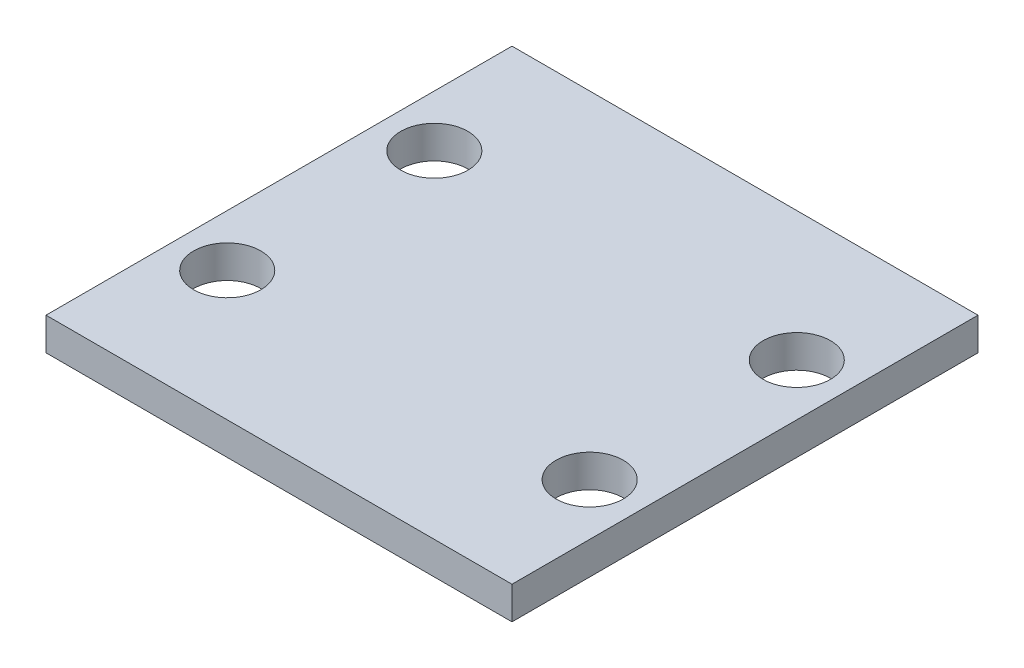
SolidWorks part; units mm, degrees
ref_plane "Front Plane" through (0, 0, 0) normal (0, 0, 1) x (1, 0, 0)
ref_plane "Top Plane" through (0, 0, 0) normal (0, 1, 0) x (1, 0, 0)
ref_plane "Right Plane" through (0, 0, 0) normal (1, 0, 0) x (0, 0, -1)
sketch "Sketch1" plane through (0, 0, 0) normal (0, 1, 0) x (1, 0, 0)
  line L1 (-11.43, -11.43) -> (11.43, -11.43)
  line L2 (-11.43, -11.43) -> (-11.43, 11.43)
  line L3 (-11.43, 11.43) -> (11.43, 11.43)
  line L4 (11.43, -11.43) -> (11.43, 11.43)
  line L5 (-11.43, -11.43) -> (11.43, 11.43) construction
  line L6 (-11.43, 11.43) -> (11.43, -11.43) construction
  line L7 (8.89, -5.08) -> (-8.89, -5.08) construction
  line L8 (8.89, -5.08) -> (8.89, 5.08) construction
  line L9 (8.89, 5.08) -> (-8.89, 5.08) construction
  line L10 (-8.89, -5.08) -> (-8.89, 5.08) construction
  line L11 (8.89, -5.08) -> (-8.89, 5.08) construction
  line L12 (8.89, 5.08) -> (-8.89, -5.08) construction
  circle A0 centre (-8.89, 5.08) radius 1.65
  circle A1 centre (-8.89, -5.08) radius 1.65
  circle A2 centre (8.89, -5.08) radius 1.65
  circle A3 centre (8.89, 5.08) radius 1.65
  point P0 (0, 0)
  point P8 (0, 0)
  dimension "D4" = 3.3
  dimension "D1" = 22.86
  dimension "D2" = 10.16
  dimension "D3" = 17.78
extrude "Boss-Extrude1" add sketch "Sketch1" along normal blind 1.6
